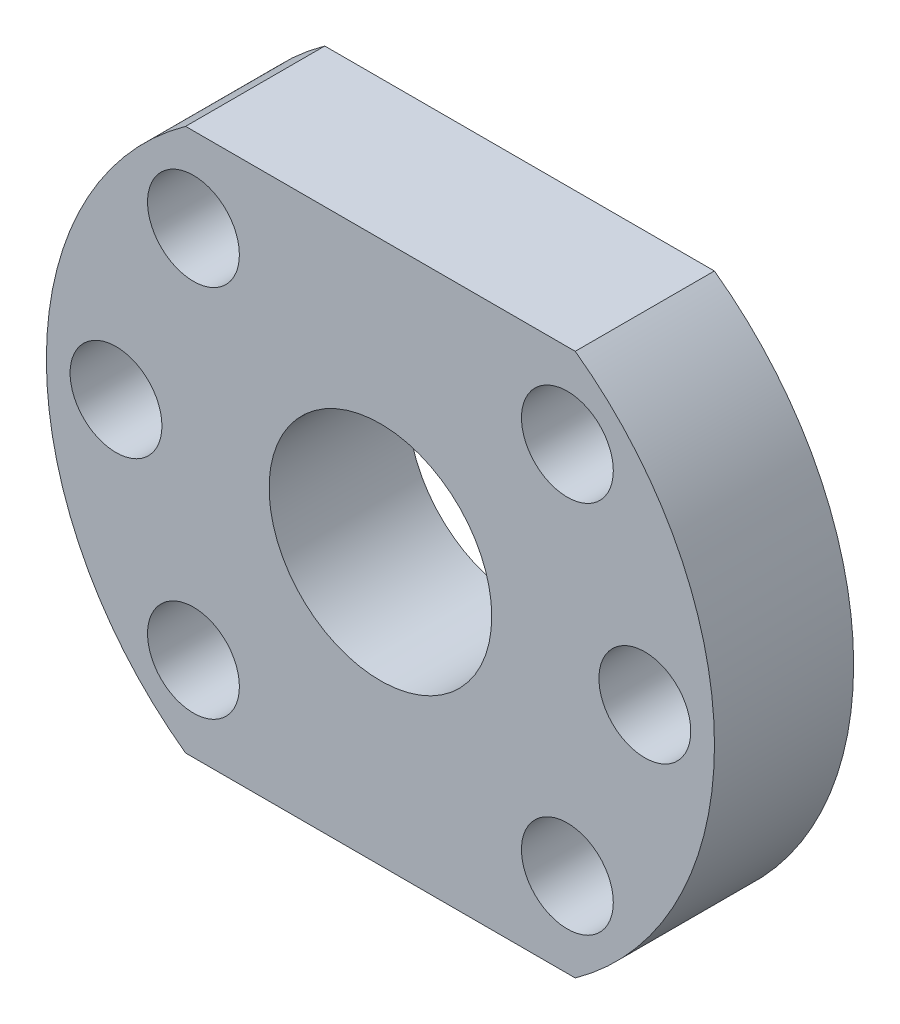
SolidWorks part; units mm, degrees
ref_plane "Front Plane" through (0, 0, 0) normal (0, 0, 1) x (1, 0, 0)
ref_plane "Top Plane" through (0, 0, 0) normal (0, 1, 0) x (1, 0, 0)
ref_plane "Right Plane" through (0, 0, 0) normal (1, 0, 0) x (0, 0, -1)
sketch "Sketch1" plane through (0, 0, 0) normal (0, 0, 1) x (1, 0, 0)
  line L0 (-14, 19.5) -> (14, 19.5)
  line L1 (14, -19.5) -> (-14, -19.5)
  line L2 (-24.0052, 0) -> (24.0052, 0) construction
  arc A0 (-14, 19.5) -> (-14, -19.5) centre (0, 0) ccw
  arc A1 (14, -19.5) -> (14, 19.5) centre (0, 0) ccw
  circle A2 centre (0, 0) radius 8
  dimension "D3" = 16
  dimension "D1" = 28
  dimension "D2" = 39
extrude "Boss-Extrude1" add sketch "Sketch1" along normal blind 10
sketch "Sketch2" plane through (0, 0, 0) normal (0, 0, 1) x (1, 0, 0)
  circle A0 centre (19, 0) radius 3.2 construction
  circle A1 centre (13.435, -13.435) radius 3.2 construction
  circle A2 centre (0, -19) radius 3.2 construction
  circle A3 centre (-13.435, -13.435) radius 3.2 construction
  circle A4 centre (-19, 0) radius 3.2 construction
  circle A5 centre (-13.435, 13.435) radius 3.2 construction
  circle A6 centre (0, 19) radius 3.2 construction
  circle A7 centre (13.435, 13.435) radius 3.2 construction
  point P2 (0, -2.3839)
  point P20 (0, 0)
  dimension "D2" = 6.4
  dimension "D1" = 19
  dimension "D3" = 8
hole_wizard "M6 Clearance Hole1" positions "Sketch3" profile "Sketch4" hole size "M6" standard "ANSI Metric" end condition through all
sketch "Sketch3" plane through (0, 0, 10) normal (0, 0, 1) x (1, 0, 0)
  point P0 (-13.435, 13.435)
  point P3 (13.435, 13.435)
  point P6 (19, 0)
  point P9 (13.435, -13.435)
  point P12 (-13.435, -13.435)
  point P15 (-19, 0)
sketch "Sketch4" plane through (-13.435, 13.435, 10) normal (1, 0, 0) x (0, -1, 0)
  line L0 (0, 0) -> (0, 10)
  line L1 (0, 10) -> (3.3, 10)
  line L2 (3.3, 10) -> (3.3, 0)
  line L5 (3.3, 0) -> (0, 0)
  line L11 (0, -6.35) -> (0, 107.95) construction
  dimension "Thru Hole Dia." = 6.6
  dimension "Thru Hole Depth" = 10
